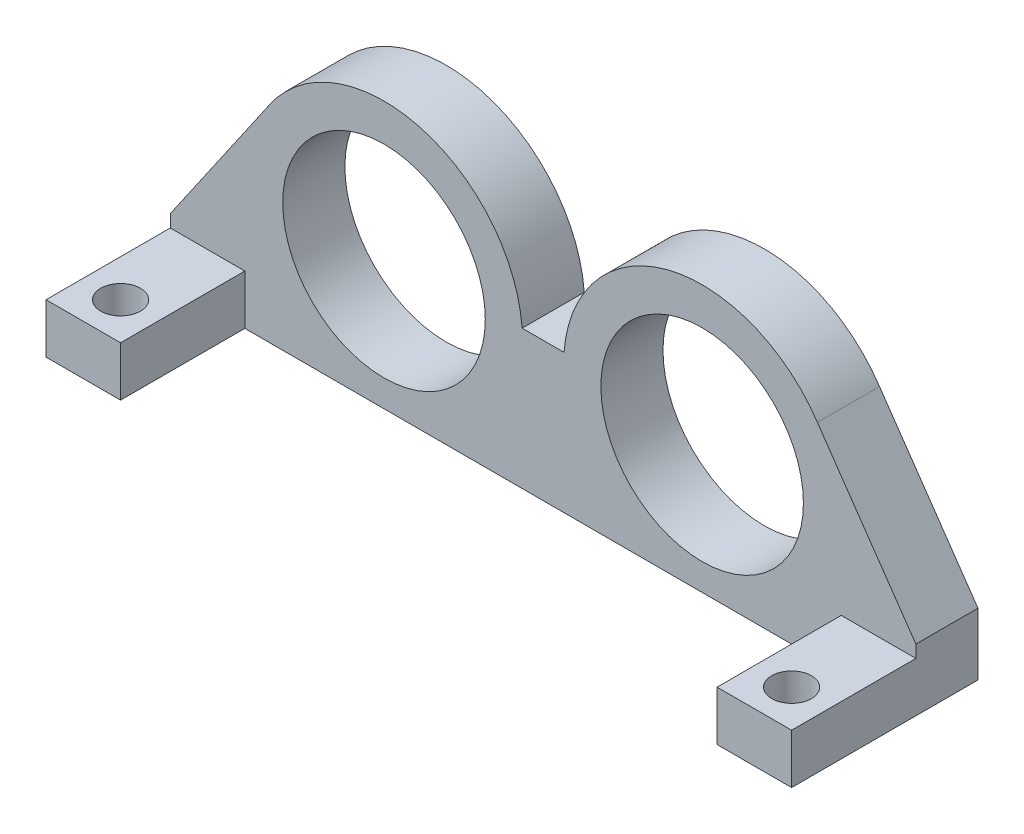
SolidWorks part; units mm, degrees
ref_plane "Front" through (0, 0, 0) normal (0, 0, 1) x (1, 0, 0)
ref_plane "Top" through (0, 0, 0) normal (0, 1, 0) x (1, 0, 0)
ref_plane "Right" through (0, 0, 0) normal (1, 0, 0) x (0, 0, -1)
sketch "Sketch1" plane through (0, 0, 0) normal (0, 0, 1) x (1, 0, 0)
  line L0 (30, 0) -> (-30, 0)
  line L1 (-30, 0) -> (-30, 5)
  line L2 (-30, 5) -> (-22.0761, 16.4859)
  line L3 (-1.6844, 11.1748) -> (1.6844, 11.1748)
  line L4 (0, 35.1636) -> (0, -9.6944) construction
  line L5 (30, 5) -> (22.0761, 16.4859)
  line L6 (30, 0) -> (30, 5)
  arc A0 (-22.0761, 16.4859) -> (-1.6844, 11.1748) centre (-12.8, 10.2991) cw
  circle A1 centre (-12.8, 10.2991) radius 8.15
  circle A2 centre (12.8, 10.2991) radius 8.15
  arc A3 (22.0761, 16.4859) -> (1.6844, 11.1748) centre (12.8, 10.2991) ccw
  point P21 (0, 11.1748)
  point P23 (0, 0)
  dimension "D1" = 16.3
  dimension "D5" = 3
  dimension "D2" = 12.8
  dimension "D3" = 60
  dimension "D4" = 5
extrude "Boss-Extrude1" add sketch "Sketch1" along normal blind 5
sketch "Sketch3" plane through (0, 0, 5) normal (0, 0, 1) x (1, 0, 0)
  line L0 (0, 24.744) -> (0, -26.2523) construction
  line L1 (-30, 0) -> (-24, 0)
  line L2 (-30, 0) -> (-30, 4)
  line L3 (-30, 4) -> (-24, 4)
  line L4 (-24, 0) -> (-24, 4)
  line L5 (24, 0) -> (24, 4)
  line L6 (30, 4) -> (24, 4)
  line L7 (30, 0) -> (30, 4)
  line L8 (30, 0) -> (24, 0)
  dimension "D1" = 4
  dimension "D2" = 6
extrude "Boss-Extrude2" add sketch "Sketch3" along normal blind 10
sketch "Sketch4" plane through (0, 4, 0) normal (0, 1, 0) x (1, 0, 0)
  line L1 (-24, -15) -> (-30, -15) construction
  line L2 (30, -15) -> (24, -15) construction
  circle A0 centre (-27, -12) radius 1.6
  circle A1 centre (27, -12) radius 1.6
  point P8 (-27, -15)
  point P9 (27, -15)
  dimension "D1" = 3.2
  dimension "D2" = 3.2
  dimension "D3" = 3
  dimension "D4" = 3
extrude "Cut-Extrude1" cut sketch "Sketch4" against normal blind 10
